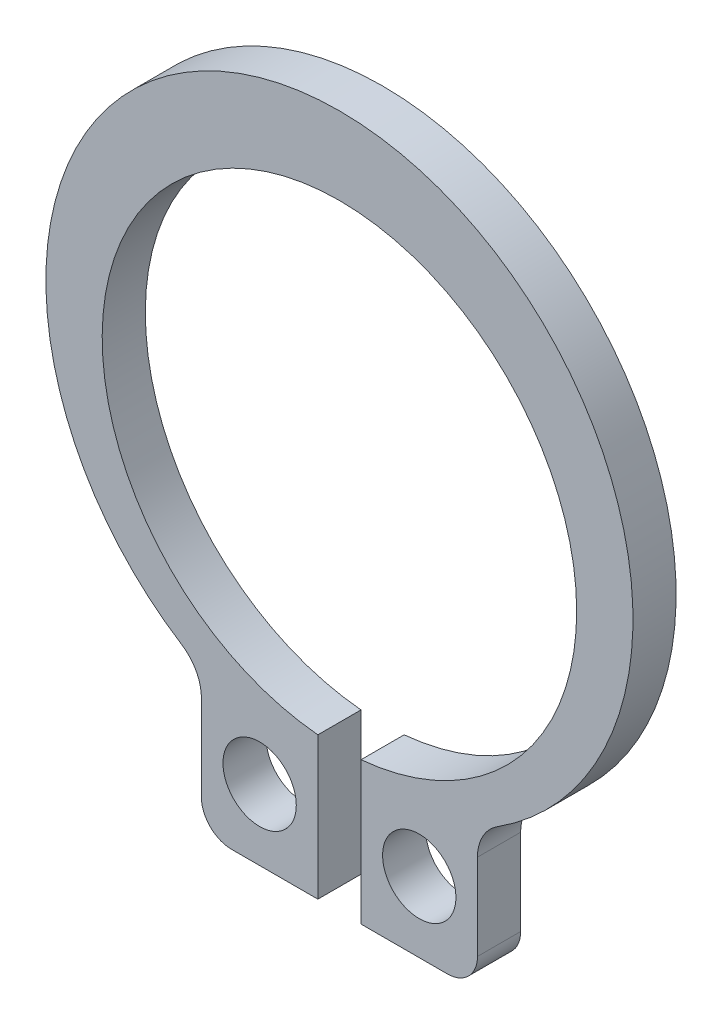
SolidWorks part; units mm, degrees
ref_plane "Front Plane" through (0, 0, 0) normal (0, 0, 1) x (1, 0, 0)
ref_plane "Top Plane" through (0, 0, 0) normal (0, 1, 0) x (1, 0, 0)
ref_plane "Right Plane" through (0, 0, 0) normal (1, 0, 0) x (0, 0, -1)
sketch "BodySke" plane through (0, 0, 0) normal (0, 0, 1) x (1, 0, 0)
  line L0 (0, 0) -> (0, 21.0564) construction
  line L1 (0, 0) -> (0, -11.0385) construction
  line L2 (-0.5, -5.4772) -> (-0.5, -8.7772)
  line L3 (-0.5, -8.7772) -> (-3.2, -8.7772)
  line L4 (-3.2, -8.7772) -> (-3.2, -5.5107)
  line L5 (3.2, -7.1439) -> (3.9811, -7.1439) construction
  line L7 (0.5, -8.7772) -> (3.2, -8.7772)
  line L8 (0.5, -5.4772) -> (0.5, -8.7772)
  line L9 (3.2, -8.7772) -> (3.2, -5.5107)
  arc A0 (0.5, -5.4772) -> (-0.5, -5.4772) centre (0, 0) ccw
  circle A2 centre (-1.85, -7.1439) radius 0.85
  circle A3 centre (1.85, -7.1439) radius 0.85
  arc A4 (3.2, -5.5107) -> (-3.2, -5.5107) centre (0, 0.495) ccw
  dimension "D1" = 0.5
  dimension "Groove_Diameter" = 11
  dimension "D2" = 0.5
  dimension "D3" = 6.805
  dimension "dia" = 1.7
  dimension "Groove_Depth" = 1.8
  dimension "Thickness" = 1
  dimension "Groove_length" = 3.3
extrude "BaseBody" add sketch "BodySke" along normal blind 1
fillet "Fillet1" radius 1 2 edges at (3.2, -5.5107, 0.5) (-3.2, -5.5107, 0.5)
fillet "Fillet2" radius 0.7 2 edges at (3.2, -8.7772, 0.5) (-3.2, -8.7772, 0.5)
equation "\"D1@BodySke\" = \"Thickness@BodySke\" / 2"
equation "\"D2@BodySke\" = \"Thickness@BodySke\" / 2"
equation "\"D3@BodySke\" =  ( \"Groove_Diameter@BodySke\" + 1.45 * \"Groove_Depth@BodySke\" )  / 2"
equation "\"Thickness@BaseBody\" = \"Thickness@BodySke\""
equation "\"D1@Fillet1\" = \"Thickness@BodySke\""
equation "\"D1@Fillet2\" = \"Thickness@BodySke\" * 0.7"
